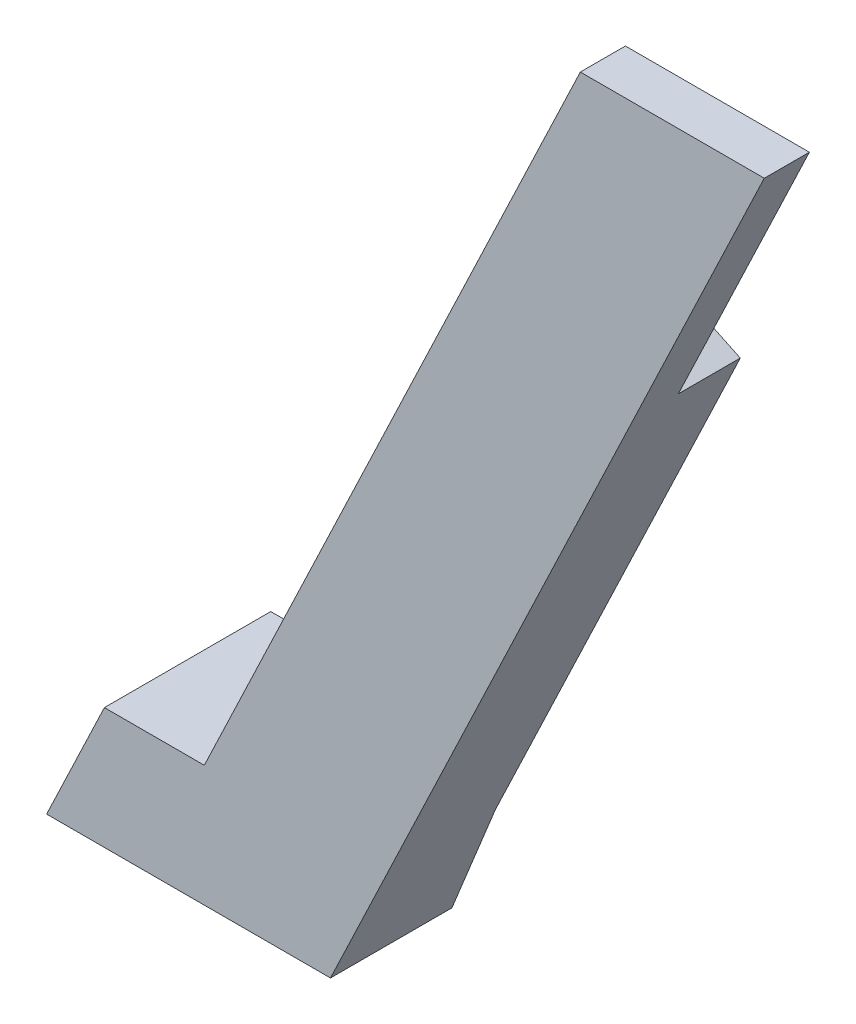
SolidWorks part; units mm, degrees
ref_plane "Front Plane" through (0, 0, 0) normal (0, 0, 1) x (1, 0, 0)
ref_plane "Top Plane" through (0, 0, 0) normal (0, 1, 0) x (1, 0, 0)
ref_plane "Right Plane" through (0, 0, 0) normal (1, 0, 0) x (0, 0, -1)
sketch "Sketch1" plane through (0, 0, 0) normal (0, 0, 1) x (1, 0, 0)
  line L0 (6.7981, 45.3856) -> (-26.5664, -24.5644)
  line L1 (6.7981, 45.3856) -> (23.1199, 45.3856)
  line L5 (-26.5664, -24.5644) -> (-35.4298, -24.5644)
  line L6 (-35.4298, -24.5644) -> (-40.5567, -35.3132)
  line L7 (-40.5567, -35.3132) -> (-15.3714, -35.3132)
  line L8 (-15.3714, -35.3132) -> (23.1199, 45.3856)
  line L9 (-66.2927, -89.2698) -> (-32.0595, -17.4985) construction
  line L10 (-26.5664, -24.5644) -> (-8.8156, 12.6508) construction
  line L11 (-16.2698, 45.3856) -> (18.3902, 45.3856) construction
  line L13 (-50.2698, -24.5644) -> (-26.5664, -24.5644) construction
extrude "Boss-Extrude1" add sketch "Sketch1" against normal blind 4
sketch "Sketch2" plane through (0, 0, -4) normal (0, 0, -1) x (-1, 0, 0)
  line L0 (0.7416, 23.646) -> (5.2189, 14.2591) construction
  line L1 (-4.3129, 21.2351) -> (0.7416, 23.646) construction
  line L2 (0.1644, 11.8482) -> (-4.3129, 21.2351) construction
  line L3 (5.2189, 14.2591) -> (0.1644, 11.8482) construction
  line L4 (0.7416, 23.646) -> (5.2189, 14.2591)
  line L5 (-4.3129, 21.2351) -> (0.7416, 23.646)
  line L6 (0.1644, 11.8482) -> (-4.3129, 21.2351)
  line L7 (5.2189, 14.2591) -> (0.1644, 11.8482)
  line L8 (50.2698, -24.5644) -> (26.5664, -24.5644) construction
  line L9 (26.5664, -24.5644) -> (8.8156, 12.6508) construction
  line L10 (8.8156, 12.6508) -> (-1.2518, 7.8489) construction
  line L11 (-1.2518, 7.8489) -> (-8.2609, 22.5438) construction
  line L12 (-8.2609, 22.5438) -> (-22.5633, 15.7219) construction
  line L13 (35.4298, -24.5644) -> (26.5664, -24.5644)
  line L14 (26.5664, -24.5644) -> (8.8156, 12.6508)
  line L15 (8.8156, 12.6508) -> (-1.2518, 7.8489)
  line L16 (-1.2518, 7.8489) -> (-8.2609, 22.5438)
  line L17 (-8.2609, 22.5438) -> (-11.4903, 21.0035)
  line L20 (15.3714, -35.3132) -> (-23.1199, 45.3856) construction
  line L21 (35.4298, -24.5644) -> (40.5567, -35.3132) construction
  line L22 (40.5567, -35.3132) -> (15.3714, -35.3132) construction
  line L23 (40.5567, -35.3132) -> (15.3714, -35.3132)
  line L24 (-11.4903, 21.0035) -> (15.3714, -35.3132)
  line M9 (-23.1199, 45.3856) -> (15.3714, -35.3132)
  line M10 (15.3714, -35.3132) -> (40.5567, -35.3132)
  line M11 (40.5567, -35.3132) -> (35.4298, -24.5644)
  line M12 (35.4298, -24.5644) -> (26.5664, -24.5644)
  line M13 (26.5664, -24.5644) -> (-6.7981, 45.3856)
extrude "Boss-Extrude2" add sketch "Sketch2" along normal up to surface (5.5 mm away) contours L16 L17 L15 M9 M10 M11 M12 M13 | L7 L4 L5 L6
sketch "Sketch3" plane through (0, 0, -9.5) normal (0, 0, -1) x (-1, 0, 0)
  line L0 (40.5567, -35.3132) -> (35.4298, -24.5644)
  line L1 (35.4298, -24.5644) -> (10.2445, -24.5644)
  line L2 (-11.4903, 21.0035) -> (15.3714, -35.3132) construction
  line L3 (10.2445, -24.5644) -> (15.3714, -35.3132)
  line L4 (15.3714, -35.3132) -> (40.5567, -35.3132)
extrude "Boss-Extrude3" add sketch "Sketch3" along normal blind 5.26
sketch "Sketch4" plane through (0, -35.3132, 0) normal (0, -1, 0) x (1, 0, 0)
  line L0 (-31.4486, -14.76) -> (-10.2445, -9.5)
  line L1 (-15.3714, -14.76) -> (-40.5567, -14.76) construction
  line L3 (-10.2445, -9.5) -> (-10.2445, -14.76)
  line L4 (-10.2445, -14.76) -> (-31.4486, -14.76)
  point P4 (-8.2698, -9.5)
  point P5 (0, 0)
  point P6 (-31.4486, -14.76)
extrude "Cut-Extrude1" cut sketch "Sketch4" against normal blind 25.26
